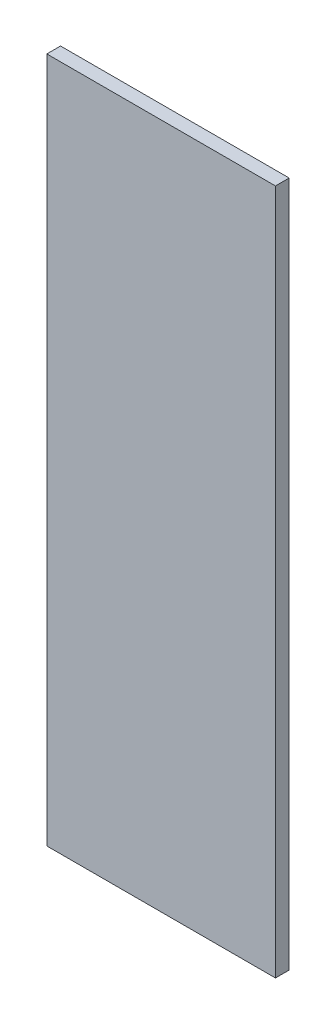
SolidWorks part; units mm, degrees
material "Plain Carbon Steel"
ref_plane "Front Plane" through (0, 0, 0) normal (0, 0, 1) x (1, 0, 0)
ref_plane "Top Plane" through (0, 0, 0) normal (0, 1, 0) x (1, 0, 0)
ref_plane "Right Plane" through (0, 0, 0) normal (1, 0, 0) x (0, 0, -1)
sketch "Sketch1" plane through (0, 0, 0) normal (0, 0, 1) x (1, 0, 0)
  line L0 (-350, -857.4627) -> (350, -857.4627) construction
  line L1 (-250, -857.4627) -> (250, -857.4627)
  line L2 (-250, -857.4627) -> (-250, 642.5373)
  line L3 (-250, 642.5373) -> (250, 642.5373)
  line L4 (250, -857.4627) -> (250, 642.5373)
  point P5 (0, -857.4627)
  dimension "D1" = 500
  dimension "D2" = 1500
extrude "Boss-Extrude1" add sketch "Sketch1" along normal blind 30 contours L2 L3 L4 L1
